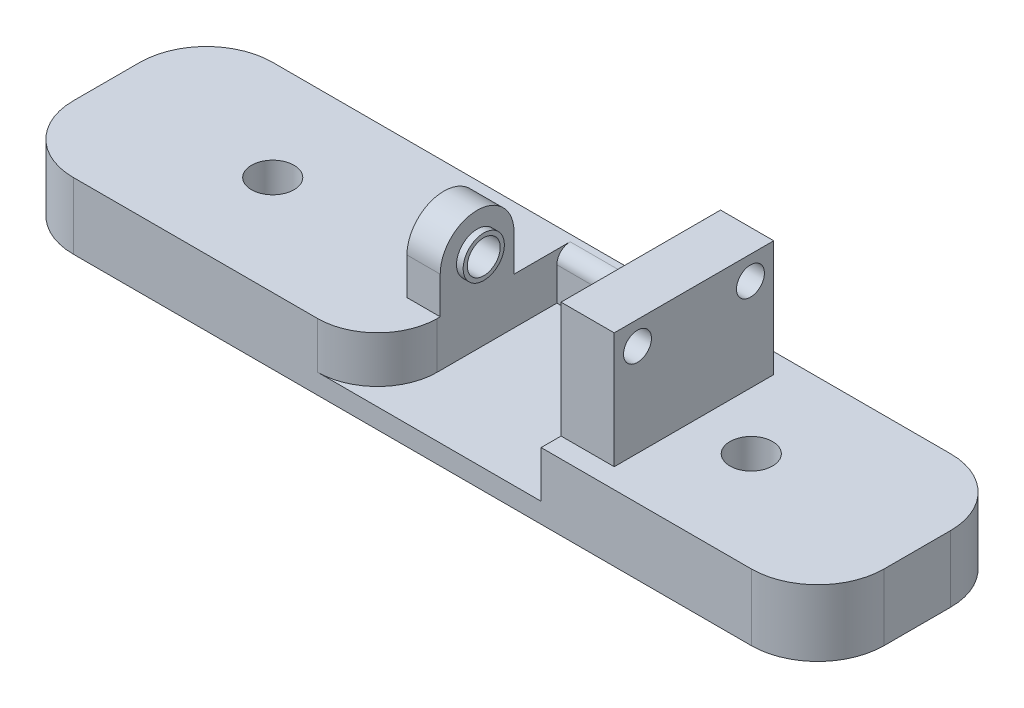
SolidWorks part; units mm, degrees
ref_plane "Front Plane" through (0, 0, 0) normal (0, 0, 1) x (1, 0, 0)
ref_plane "Top Plane" through (0, 0, 0) normal (0, 1, 0) x (1, 0, 0)
ref_plane "Right Plane" through (0, 0, 0) normal (1, 0, 0) x (0, 0, -1)
sketch "Sketch1" plane through (0, 0, 0) normal (0, 1, 0) x (1, 0, 0)
  line L1 (-61, 15) -> (61, 15)
  line L2 (-61, 15) -> (-61, -15)
  line L3 (-61, -15) -> (61, -15)
  line L4 (61, 15) -> (61, -15)
  line L5 (-61, 15) -> (61, -15) construction
  line L6 (-61, -15) -> (61, 15) construction
  point P0 (0, 0)
  dimension "D1" = 122
  dimension "D2" = 30
extrude "Boss-Extrude1" add sketch "Sketch1" along normal blind 10
ref_plane "Plane1" through (0, 0, 0) normal (1, 0, 0) x (0, 0, -1)
ref_plane "Plane2" through (19.38, 0, 0) normal (1, 0, 0) x (0, 0, -1)
ref_plane "Plane3" through (-5.25, 0, 0) normal (1, 0, 0) x (0, 0, -1)
sketch "Sketch2" plane through (19.38, 0, 0) normal (1, 0, 0) x (0, 0, -1)
  line L0 (-15, 10) -> (15, 10) construction
  line L5 (-12, 10) -> (12, 10)
  line L6 (-12, 10) -> (-12, 27.4478)
  line L7 (-12, 27.4478) -> (12, 27.4478)
  line L8 (12, 10) -> (12, 27.4478)
  point P7 (0, 27.4478)
  dimension "D1" = 24
  dimension "D2" = 17.4478
extrude "Boss-Extrude2" add sketch "Sketch2" along normal blind 8
sketch "Sketch3" plane through (-5.25, 0, 0) normal (1, 0, 0) x (0, 0, -1)
  line L0 (-5.5522, 15.5522) -> (-5.5522, 10)
  line L1 (-15, 10) -> (15, 10) construction
  line L3 (-5.5522, 10) -> (5.5522, 10)
  line L4 (5.5522, 10) -> (5.5522, 15.5522)
  circle A0 centre (0, 15.5522) radius 2.475
  arc A1 (5.5522, 15.5522) -> (-5.5522, 15.5522) centre (0, 15.5522) ccw
  point P3 (0, 0)
  point P8 (0, 0)
  dimension "D1" = 4.95
  dimension "D2" = 5.5522
extrude "Boss-Extrude3" add sketch "Sketch3" against normal blind 5
sketch "Sketch4" plane through (0, 10, 0) normal (0, 1, 0) x (1, 0, 0)
  line L0 (-61, -15) -> (61, -15) construction
  line L1 (-5.25, 12) -> (19.38, 12)
  line L2 (-5.25, 12) -> (-5.25, -15)
  line L3 (-5.25, -15) -> (19.38, -15)
  line L4 (19.38, 12) -> (19.38, -15)
  line L5 (19.38, -12) -> (19.38, 12) construction
  point P0 (-5.25, 5.5522)
  dimension "D1" = 27
extrude "Cut-Extrude1" cut sketch "Sketch4" against normal blind 7
fillet "Fillet1" radius 10 4 edges at (-61, 5, -15) (-61, 5, 15) (61, 5, -15) (61, 5, 15)
sketch "Sketch7" plane through (0, 10, 0) normal (0, 1, 0) x (1, 0, 0)
  line L0 (-61, 5) -> (-61, -5) construction
  line L1 (0, 0) -> (0, 29.2953) construction
  circle A0 centre (-36, 0) radius 3.2
  circle A1 centre (36, 0) radius 3.2
  point P2 (-61, 0)
  dimension "D1" = 6.4
  dimension "D2" = 25
extrude "Cut-Extrude2" cut sketch "Sketch7" against normal through all
sketch "Sketch8" plane through (-5.25, 0, 0) normal (1, 0, 0) x (0, 0, -1)
  circle A0 centre (0, 15.5522) radius 2.475
  circle A1 centre (0, 15.5522) radius 3.1
  dimension "D1" = 4.95
  dimension "D2" = 6.2
extrude "Boss-Extrude5" add sketch "Sketch8" along normal blind 1
fillet "Fillet2" radius 9 1 edges at (-5.25, 6.5, 15)
fillet "Fillet3" radius 2 1 edges at (7.065, 10, -12)
sketch "Sketch9" plane through (19.38, 0, 0) normal (-1, 0, 0) x (0, 0, 1)
  line L0 (12, 27.4478) -> (12, 10) construction
  line L1 (-12, 27.4478) -> (12, 27.4478) construction
  line L2 (-12, 27.4478) -> (-12, 3.4478) construction
  line L3 (-12, 3.4478) -> (12, 3.4478) construction
  line L4 (12, 27.4478) -> (12, 3.4478) construction
  line L5 (-12, 27.4478) -> (12, 3.4478) construction
  line L6 (-12, 3.4478) -> (12, 27.4478) construction
  circle A0 centre (8.5, 23.9478) radius 2.1
  circle A1 centre (8.5, 6.9478) radius 2.1
  circle A2 centre (-8.5, 6.9478) radius 2.1
  circle A3 centre (-8.5, 23.9478) radius 2.1
  point P7 (0, 15.4478)
  dimension "D2" = 8.5
  dimension "D3" = 4.2
  dimension "D1" = 24
  dimension "D4" = 4
extrude "Cut-Extrude3" cut sketch "Sketch9" against normal blind 8
